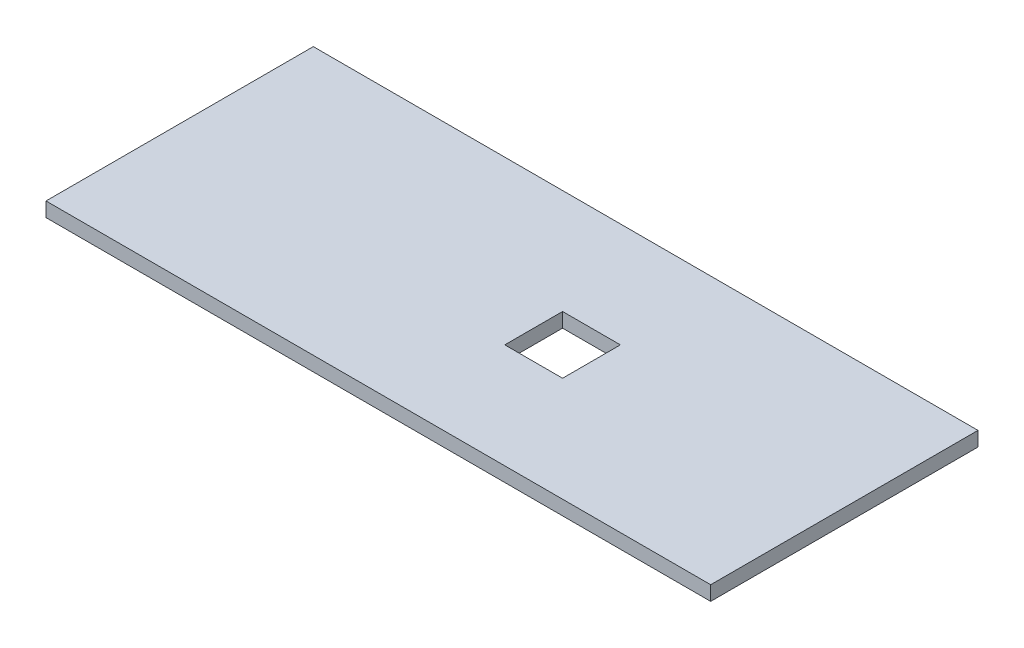
SolidWorks part; units mm, degrees
ref_plane "Front Plane" through (0, 0, 0) normal (0, 0, 1) x (1, 0, 0)
ref_plane "Top Plane" through (0, 0, 0) normal (0, 1, 0) x (1, 0, 0)
ref_plane "Right Plane" through (0, 0, 0) normal (1, 0, 0) x (0, 0, -1)
sketch "Sketch1" plane through (0, 0, 0) normal (0, 0, 1) x (1, 0, 0)
  line L0 (0, 0) -> (0, 4)
  line L1 (0, 0) -> (-184, 0)
  line L2 (-184, 0) -> (-184, 4)
  line L3 (-184, 4) -> (0, 4)
extrude "Boss-Extrude1" add sketch "Sketch1" along normal blind 74
sketch "Sketch2" plane through (0, 4, 0) normal (0, 1, 0) x (1, 0, 0)
  line L0 (0, 0) -> (0, -37) construction
  line L1 (0, -74) -> (0, 0) construction
  line L2 (0, -37) -> (-70, -37) construction
  line L3 (-70, -37) -> (-70, -29)
  line L4 (-70, -37) -> (-70, -45)
  line L5 (-70, -29) -> (-86, -29)
  line L6 (-86, -29) -> (-86, -45)
  line L7 (-86, -45) -> (-70, -45)
  dimension "D1" = 70
  dimension "D2" = 16
  dimension "D3" = 16
extrude "Cut-Extrude1" cut sketch "Sketch2" against normal blind 74
